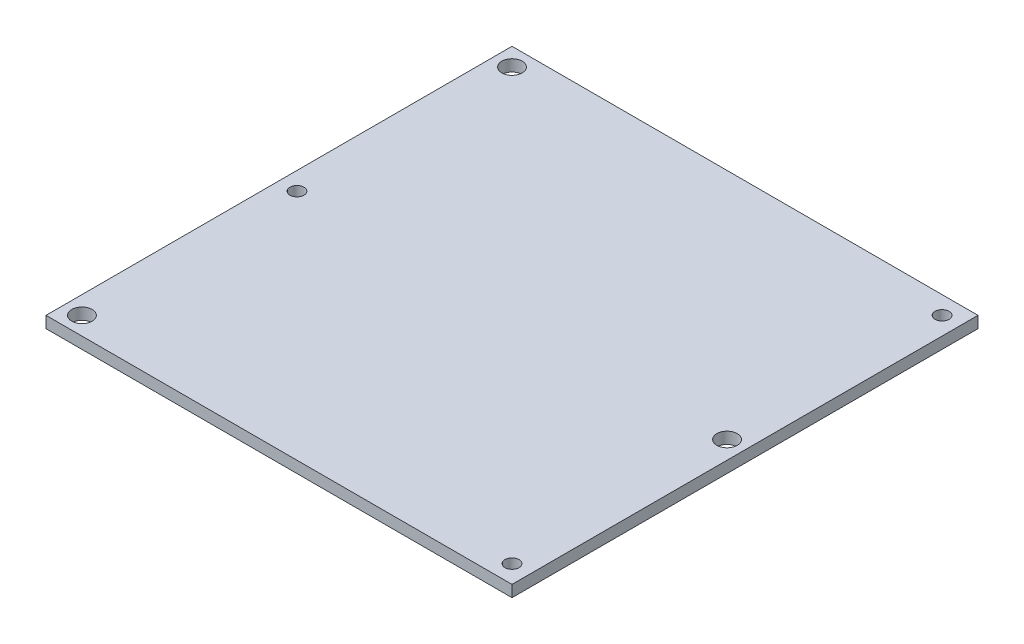
SolidWorks part; units mm, degrees
material "Pine"
ref_plane "Front Plane" through (0, 0, 0) normal (0, 0, 1) x (1, 0, 0)
ref_plane "Top Plane" through (0, 0, 0) normal (0, 1, 0) x (1, 0, 0)
ref_plane "Right Plane" through (0, 0, 0) normal (1, 0, 0) x (0, 0, -1)
sketch "Sketch1" plane through (0, 0, 0) normal (0, 1, 0) x (1, 0, 0)
  line L1 (171.45, -171.45) -> (-171.45, -171.45)
  line L2 (171.45, -171.45) -> (171.45, 171.45)
  line L3 (171.45, 171.45) -> (-171.45, 171.45)
  line L4 (-171.45, -171.45) -> (-171.45, 171.45)
  line L5 (171.45, -171.45) -> (-171.45, 171.45) construction
  line L6 (171.45, 171.45) -> (-171.45, -171.45) construction
  point P0 (0, 0)
  dimension "D1" = 342.9
extrude "Boss-Extrude1" add sketch "Sketch1" along normal blind 8.5
sketch "Sketch2" plane through (0, 8.5, 0) normal (0, 1, 0) x (1, 0, 0)
  line L0 (-158.225, 158.225) -> (158.225, -158.225) construction
  line L1 (158.225, 158.225) -> (-158.225, -158.225) construction
  line L2 (-145, 0) -> (-171.45, 0) construction
  line L3 (145, -145) -> (-145, -145) construction
  line L4 (145, -145) -> (145, 145) construction
  line L5 (145, 145) -> (-145, 145) construction
  line L6 (-145, -145) -> (-145, 145) construction
  line L7 (145, -145) -> (-145, 145) construction
  line L8 (145, 145) -> (-145, -145) construction
  line L9 (-171.45, 171.45) -> (-171.45, -171.45) construction
  circle A0 centre (-158.225, 158.225) radius 4
  circle A1 centre (-158.225, 0) radius 4
  circle A2 centre (-158.225, -158.225) radius 4
  circle A3 centre (158.225, 158.225) radius 4
  circle A4 centre (158.225, 0) radius 4
  circle A5 centre (158.225, -158.225) radius 4
  point P13 (0, 0)
  dimension "D1" = 8
  dimension "D2" = 290
extrude "Cut-Extrude1" cut sketch "Sketch2" against normal through all
sketch "Sketch3" plane through (0, 8.5, 0) normal (0, 1, 0) x (1, 0, 0)
  circle A0 centre (-158.225, 158.225) radius 7.5
  circle A2 centre (-158.225, -158.225) radius 7.5
  circle A3 centre (-158.225, 0) radius 5.15
  circle A4 centre (158.225, 0) radius 7.5
  circle A5 centre (158.225, 158.225) radius 5.15
  circle A6 centre (158.225, -158.225) radius 5.15
  dimension "D1" = 15
  dimension "D2" = 10.3
  dimension "D3" = 15
extrude "Cut-Extrude3" cut sketch "Sketch3" against normal blind 10
